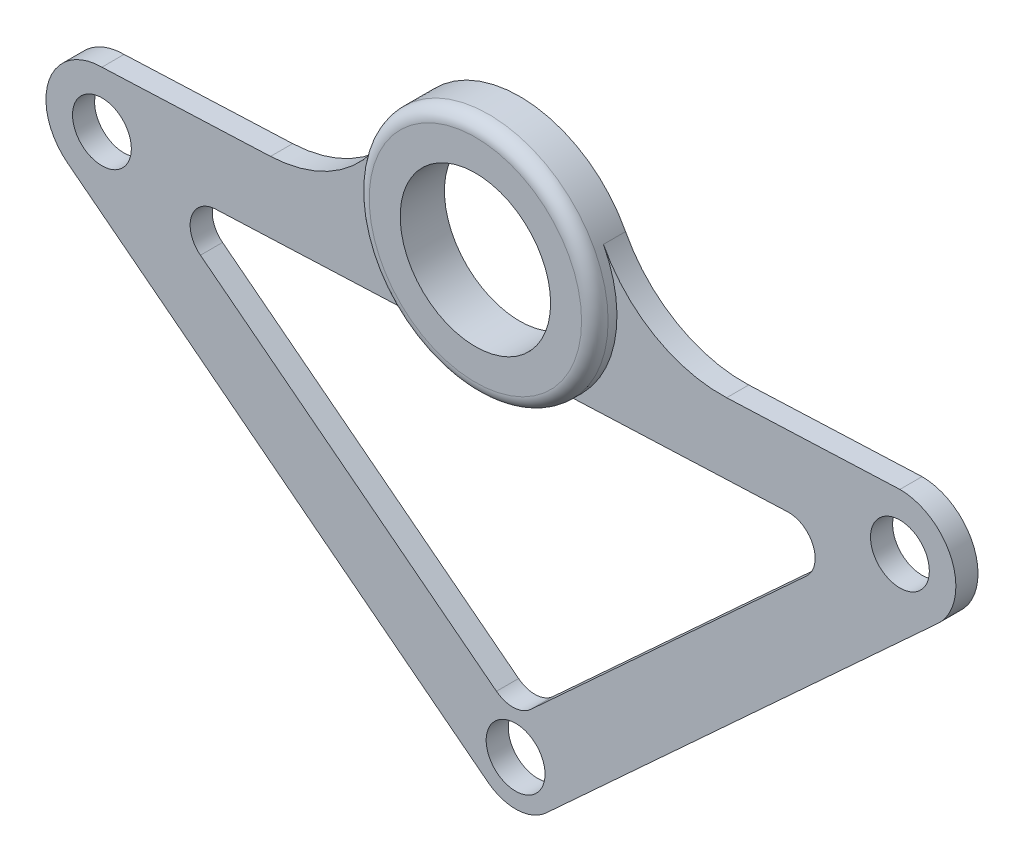
SolidWorks part; units mm, degrees
ref_plane "Front Plane" through (0, 0, 0) normal (0, 0, 1) x (1, 0, 0)
ref_plane "Top Plane" through (0, 0, 0) normal (0, 1, 0) x (1, 0, 0)
ref_plane "Right Plane" through (0, 0, 0) normal (1, 0, 0) x (0, 0, -1)
sketch "Sketch1" plane through (0, 0, 0) normal (0, 0, 1) x (1, 0, 0)
  line L0 (57.5247, 15.0168) -> (37.9425, 14.1987)
  line L1 (44.8204, 6.4791) -> (-19.8121, 3.7789)
  line L2 (-21.5254, -1.5891) -> (11.9313, -27.5371)
  line L3 (15.7998, -27.3755) -> (46.9755, 1.2727)
  line L4 (-31.6301, 6.2478) -> (15.8829, -30.6018) construction
  line L5 (-36.5329, -0.0738) -> (10.9801, -36.9234)
  line L6 (17.5306, -36.6497) -> (61.8044, 4.0346)
  line L7 (60.6221, 14.2065) -> (26.9742, 33.1051)
  line L8 (26.9742, 33.1051) -> (-20.235, 31.1328)
  line L9 (-20.235, 31.1328) -> (-37.6439, 8.8143)
  line L10 (-36.5329, -0.0738) -> (10.9801, -36.9234)
  line L11 (17.5306, -36.6497) -> (61.8044, 4.0346)
  line L12 (57.8586, 7.0238) -> (-32.3227, 3.2562) construction
  line L13 (12.1176, -30.7591) -> (56.3913, 9.9252) construction
  line L15 (-13.602, 12.0453) -> (-32.6566, 11.2492)
  line L16 (57.5247, 15.0168) -> (-32.6566, 11.2492) construction
  circle A0 centre (-32.6566, 4.9242) radius 3.325 construction
  circle A1 centre (14.0933, -32.9092) radius 3.325 construction
  circle A2 centre (57.5247, 8.6918) radius 3.325 construction
  circle A3 centre (-32.6566, 4.9242) radius 3.325
  circle A4 centre (14.0933, -32.9092) radius 3.325
  circle A5 centre (57.5247, 8.6918) radius 3.325
  arc A6 (-32.6566, 11.2492) -> (-36.5329, -0.0738) centre (-32.6566, 4.9242) ccw
  arc A7 (61.8044, 4.0346) -> (56.9971, 14.9948) centre (57.5247, 8.6918) ccw
  arc A8 (11.9313, -27.5371) -> (15.7998, -27.3755) centre (13.7699, -25.1665) ccw
  arc A9 (-37.6439, 8.8143) -> (-36.5329, -0.0738) centre (-32.6566, 4.9242) ccw
  arc A10 (10.9801, -36.9234) -> (17.5306, -36.6497) centre (14.0933, -32.9092) ccw
  arc A11 (61.8044, 4.0346) -> (60.6221, 14.2065) centre (57.5247, 8.6918) ccw
  arc A13 (10.9801, -36.9234) -> (17.5306, -36.6497) centre (14.0933, -32.9092) ccw
  arc A14 (46.9755, 1.2727) -> (44.8204, 6.4791) centre (44.9456, 3.4817) ccw
  arc A15 (-21.5254, -1.5891) -> (-19.8121, 3.7789) centre (-19.6868, 0.7815) cw
  circle A16 centre (12.05, 16) radius 8.5 construction
  circle A17 centre (12.05, 16) radius 8.5
  arc A18 (24.0183, 22.2458) -> (-0.3975, 21.2258) centre (12.05, 16) ccw
  circle A19 centre (12.05, 16) radius 13.5 construction
  arc A20 (-13.602, 12.0453) -> (-0.3975, 21.2258) centre (-14.2281, 27.0322) ccw
  arc A21 (24.0183, 22.2458) -> (37.9425, 14.1987) centre (37.3164, 29.1856) ccw
  dimension "D3" = 3
  dimension "D5" = 15
  dimension "D6" = 15
  dimension "D1" = 0
  dimension "D2" = 8
  dimension "D4" = 5
extrude "Boss-Extrude1" add sketch "Sketch1" along normal mid plane 5 contours A21 A18 A20 L15 A6 L10 A13 L11 A7 L0 A17 A5 A4 A3 L2 A15 L1 A14 L3 A8
sketch "Sketch2" plane through (0, 0, 2.5) normal (0, 0, 1) x (1, 0, 0)
  circle A0 centre (12.05, 16) radius 13.5
  arc A1 (24.0183, 22.2458) -> (-0.3975, 21.2258) centre (12.05, 16) ccw construction
  circle A2 centre (12.05, 16) radius 70.9119
extrude "Cut-Extrude1" cut sketch "Sketch2" against normal blind 2.5
sketch "Sketch3" plane through (0, 0, 2.5) normal (0, 0, 1) x (1, 0, 0)
  circle A0 centre (12.05, 16) radius 13.5
  circle A1 centre (12.05, 16) radius 8.5
  circle A2 centre (12.05, 16) radius 8.5 construction
  arc A3 (20.4887, 5.4626) -> (4.5196, 4.7954) centre (12.05, 16) ccw construction
extrude "Boss-Extrude2" add sketch "Sketch3" against normal up to surface (5 mm away) up to face at (12.621, 3.1828, -2.5)
fillet "Fillet1" radius 1.5 1 edges at (25.55, 16, 2.5)
